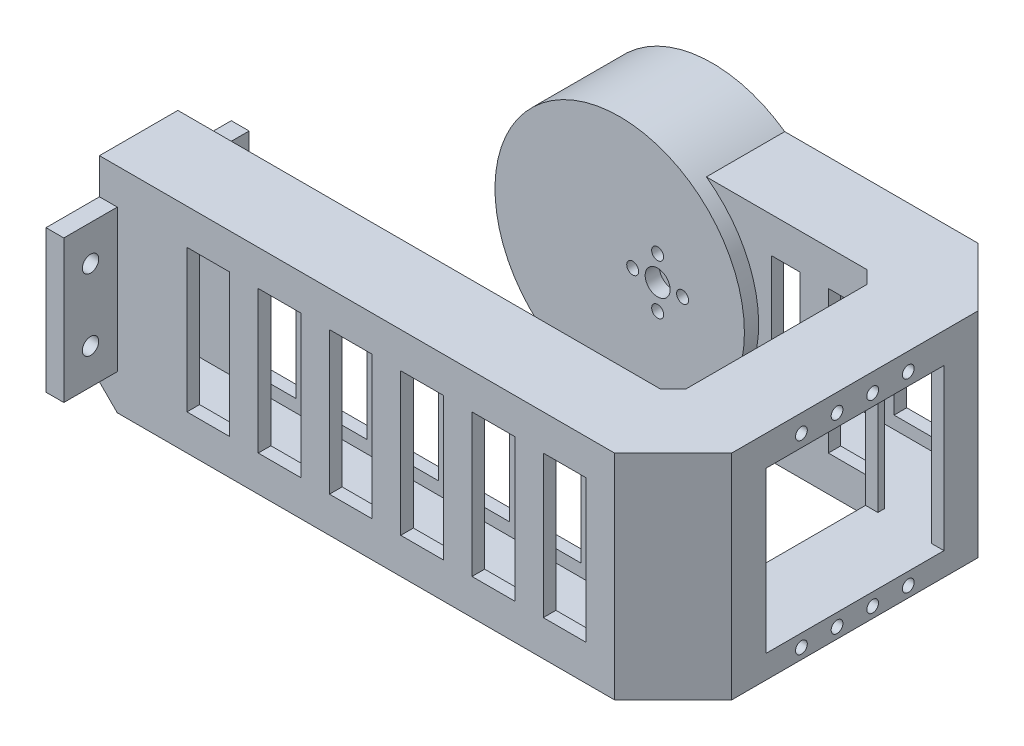
SolidWorks part; units mm, degrees
ref_plane "Plan de face" through (0, 0, 0) normal (0, 0, 1) x (1, 0, 0)
ref_plane "Plan de dessus" through (0, 0, 0) normal (0, 1, 0) x (1, 0, 0)
ref_plane "Plan de droite" through (0, 0, 0) normal (1, 0, 0) x (0, 0, -1)
sketch "Esquisse1" plane through (0, 0, 0) normal (0, 0, 1) x (1, 0, 0)
  circle A0 centre (0, 0) radius 35
  dimension "D1" = 70
extrude "Boss.-Extru.2" add sketch "Esquisse1" along normal blind 26
sketch "Esquisse4" plane through (0, 0, 0) normal (1, 0, 0) x (0, 0, -1)
  line L0 (-18.5, 16.6184) -> (-18.5, -18.3816)
  line L1 (-21.7349, 0) -> (0, 0) construction
  line L2 (-3.5, 16.6184) -> (-3.5, -18.3816)
  line L4 (0, 36.85) -> (0, -36.85) construction
  arc A0 (-18.5, 16.6184) -> (-3.5, 16.6184) centre (-11, 6) cw
  arc A1 (-18.5, -18.3816) -> (-3.5, -18.3816) centre (-11, -7.7632) ccw
  dimension "D3" = 3.5
  dimension "D4" = 13
  dimension "D7" = 6
  dimension "D2" = 15
  dimension "D1" = 15
  dimension "D5" = 35
  dimension "D6" = 0
  dimension "D8" = 16.6184
  dimension "D9" = 7.7632
extrude "Enlèv. mat.-Extru.6" cut sketch "Esquisse4" along normal blind 35
sketch "Esquisse5" plane through (0, 0, 0) normal (1, 0, 0) x (0, 0, -1)
  line L0 (-18.55, 20) -> (-18.55, -25)
  line L1 (-18.55, -25) -> (-3.55, -25)
  line L2 (-3.55, -25) -> (-3.55, 20)
  line L3 (-18.55, 20) -> (-3.55, 20)
  line L4 (0, 55) -> (0, -55) construction
  line L5 (-26, -35) -> (0, -35) construction
  line L7 (-22, 28.5) -> (0, 28.5)
  line L8 (-22, 28.5) -> (-22, -31.5)
  line L9 (-22, -31.5) -> (0, -31.5)
  line L10 (0, 28.5) -> (0, -31.5)
  line L11 (-22, 28.5) -> (0, -31.5) construction
  line L12 (-22, -31.5) -> (0, 28.5) construction
  point P8 (-11, -1.5)
  dimension "D1" = 15
  dimension "D2" = 3.55
  dimension "D3" = 45
  dimension "D4" = 10
  dimension "D5" = 0
  dimension "D6" = 3.5
  dimension "D7" = 60
  dimension "D8" = 22
sketch3d "Esquisse3D6"
  line L0 (0, -1.5, 11) -> (70, -1.5, 11)
  line L1 (70, -1.5, 11) -> (80, -1.5, 21)
  line L2 (80, -1.5, 81) -> (70, -1.5, 91)
  line L6 (80, -1.5, 21) -> (80, -1.5, 81)
  line L7 (70, -1.5, 91) -> (-70, -1.5, 91)
  point P1 (80, -1.5, 11)
  point P3 (80, -1.5, 91)
  dimension "D1" = 80
  dimension "D3" = 80
  dimension "D4" = 150
sweep "Balayage16" add profiles "Esquisse5" path "Esquisse3D6"
sketch "Esquisse7" plane through (0, 0, 0) normal (1, 0, 0) x (0, 0, -1)
  line L0 (55, 0) -> (-55, 0) construction
  line L1 (0, -30) -> (-22, -30)
  line L2 (0, -30) -> (0, 30)
  line L3 (0, 30) -> (-22, 30)
  line L4 (-22, -30) -> (-22, 30)
  line L5 (0, -30) -> (-22, 30) construction
  line L6 (0, 30) -> (-22, -30) construction
  line L7 (0, -35) -> (0, 35) construction
  line L8 (-26, -35) -> (0, -35) construction
  line L9 (-4, 20) -> (-19, 20)
  line L10 (-4, 20) -> (-4, -25)
  line L11 (-4, -25) -> (-19, -25)
  line L12 (-19, 20) -> (-19, -25)
  point P0 (-11, 0)
  dimension "D1" = 0
  dimension "D2" = 22
  dimension "D3" = 60
  dimension "D4" = 4
  dimension "D5" = 10
  dimension "D6" = 45
  dimension "D7" = 15
extrude "Enlèv. mat.-Extru.11" cut sketch "Esquisse7" along normal blind 11
sketch "Esquisse9" plane through (0, 0, 0) normal (0, 0, -1) x (-1, 0, 0)
  circle A0 centre (0, 0) radius 31.5
  dimension "D1" = 63
extrude "Enlèv. mat.-Extru.12" cut sketch "Esquisse9" against normal blind 18.8
sketch "Esquisse10" plane through (0, 0, 26) normal (0, 0, 1) x (1, 0, 0)
  line L0 (0, 8.8008) -> (0, -8.9311) construction
  line L1 (55, 0) -> (-55, 0) construction
  line L2 (-21, 11) -> (-21, -11) construction
  line L3 (-21, -11) -> (21, -11) construction
  line L4 (-21, 11) -> (21, 11) construction
  line L5 (21, 11) -> (21, -11) construction
  line L6 (3.65, 0) -> (17.65, 0) construction
  line L7 (-21, -11) -> (21, 11) construction
  line L8 (-21, 11) -> (21, -11) construction
  line L9 (10.65, 0) -> (10.65, 8.8008) construction
  line L10 (10.65, 0) -> (10.65, -8.9311) construction
  line L11 (12.325, -7) -> (6.1002, -7) construction
  line L12 (12.325, 7) -> (6.6662, 7) construction
  circle A0 centre (10.65, 0) radius 3.5
  circle A2 centre (17.65, 0) radius 1.675
  circle A3 centre (3.65, 0) radius 1.675
  circle A5 centre (10.65, -7) radius 1.675
  circle A6 centre (10.65, 7) radius 1.675
  point P4 (0, 0)
  dimension "D2" = 7
  dimension "D9" = 7
  dimension "D10" = 3.35
  dimension "D12" = 3.35
  dimension "D14" = 3.35
  dimension "D5" = 3.35
  dimension "D7" = 7
  dimension "D8" = 7
  dimension "D6" = 7
  dimension "D15" = 3.35
  dimension "D3" = 22
  dimension "D4" = 42
extrude "Enlèv. mat.-Extru.13" cut sketch "Esquisse10" against normal blind 10
sketch "Esquisse12" plane through (0, 0, 0) normal (1, 0, 0) x (0, 0, -1)
  line L0 (-76, 20) -> (-26, 20)
  line L1 (-26, 20) -> (-26, -25)
  line L2 (-26, -25) -> (-76, -25)
  line L3 (-16.4437, 28.5) -> (-85.5563, 28.5) construction
  line L4 (-16.4437, -31.5) -> (-85.5563, -31.5) construction
  line L14 (-76, 20) -> (-76, -25)
  circle A0 centre (-66, -28.5) radius 1.65
  circle A1 centre (-36, -28.5) radius 1.65
  circle A2 centre (-46, -28.5) radius 1.65
  circle A3 centre (-56, -28.5) radius 1.65
  circle A4 centre (-66, 23.5) radius 1.65
  circle A5 centre (-56, 23.5) radius 1.65
  circle A6 centre (-46, 23.3) radius 1.65
  circle A7 centre (-36, 23.5) radius 1.65
  dimension "D5" = 3.3
  dimension "D6" = 3.3
  dimension "D11" = 3.3
  dimension "D12" = 3.3
  dimension "D17" = 3.3
  dimension "D18" = 3.3
  dimension "D19" = 3.3
  dimension "D20" = 3.3
  dimension "D1" = 8.5
  dimension "D2" = 6.5
  dimension "D3" = 26
  dimension "D4" = 50
  dimension "D7" = 3.5
  dimension "D8" = 3.5
  dimension "D9" = 10
  dimension "D10" = 10
  dimension "D13" = 3.5
  dimension "D14" = 3.5
  dimension "D15" = 10
  dimension "D16" = 10
  dimension "D21" = 10
  dimension "D22" = 10
  dimension "D23" = 10
  dimension "D24" = 10
  dimension "D25" = 3.5
  dimension "D26" = 3.5
  dimension "D27" = 3.3
  dimension "D28" = 3.5
extrude "Enlèv. mat.-Extru.16" cut sketch "Esquisse12" along normal blind 100
sketch "Esquisse14" plane through (0, 0, 0) normal (0, 0, -1) x (-1, 0, 0)
  line L0 (-74.5563, -31.5) -> (-74.5563, 28.5) construction
  line L1 (-54.5563, 18.5) -> (-66.5563, 18.5)
  line L2 (-66.5563, 18.5) -> (-66.5563, -21.5)
  line L3 (-66.5563, -21.5) -> (-54.5563, -21.5)
  line L4 (-74.5563, -31.5) -> (70, -31.5) construction
  line L5 (-74.5563, -31.5) -> (-15.2561, -31.5) construction
  line L6 (-46.5563, -21.5) -> (-38.5563, -21.5)
  line L7 (-46.5563, -21.5) -> (-46.5563, 18.5)
  line L8 (-46.5563, 18.5) -> (-38.5563, 18.5)
  line L9 (-38.5563, -21.5) -> (-38.5563, 18.5)
  line L10 (-54.5563, 18.5) -> (-54.5563, -21.5)
  line L11 (-46.5563, -21.5) -> (-38.5563, 18.5) construction
  line L12 (-46.5563, 18.5) -> (-38.5563, -21.5) construction
  point P4 (-42.5563, -1.5)
  dimension "D1" = 8
  dimension "D2" = 12
  dimension "D3" = 10
  dimension "D4" = 8
  dimension "D5" = 8
  dimension "D6" = 10
  dimension "D7" = 40
  dimension "D10" = 40
extrude "Enlèv. mat.-Extru.17" cut sketch "Esquisse14" against normal blind 40
chamfer "Chanfrein1" distance 5 angle 45 1 edges at (-70, -31.5, 91)
sketch "Esquisse18" plane through (0, 0, 102) normal (0, 0, 1) x (1, 0, 0)
  line L1 (54.5563, 18.5) -> (66.5563, 18.5)
  line L2 (66.5563, -21.5) -> (54.5563, -21.5)
  line L3 (-13.4437, 18.5) -> (-13.4437, -21.5)
  line L4 (66.5563, 18.5) -> (66.5563, -21.5)
  line L5 (34.5563, 18.5) -> (46.5563, 18.5)
  line L6 (54.5563, 18.5) -> (54.5563, -21.5)
  line L7 (34.5563, -21.5) -> (46.5563, -21.5)
  line L8 (74.5563, -31.5) -> (-65, -31.5) construction
  line L9 (-13.4437, -21.5) -> (-25.4437, -21.5)
  line L10 (74.5563, 28.5) -> (-70, 28.5) construction
  line L11 (14.5563, 18.5) -> (26.5563, 18.5)
  line L12 (-5.4437, 18.5) -> (6.5563, 18.5)
  line L13 (-5.4437, 18.5) -> (-5.4437, -21.5)
  line L14 (-5.4437, -21.5) -> (6.5563, -21.5)
  line L15 (6.5563, 18.5) -> (6.5563, -21.5)
  line L16 (26.5563, -21.5) -> (14.5563, -21.5)
  line L17 (14.5563, 18.5) -> (14.5563, -21.5)
  line L18 (-25.4437, -21.5) -> (-25.4437, 18.5)
  line L19 (-25.4437, 18.5) -> (-13.4437, 18.5)
  line L20 (74.5563, 28.5) -> (74.5563, -31.5) construction
  line L22 (-45.4437, -21.5) -> (-33.4437, -21.5)
  line L23 (26.5563, 18.5) -> (26.5563, -21.5)
  line L24 (-45.4437, -21.5) -> (-45.4437, 18.5)
  line L25 (34.5563, 18.5) -> (34.5563, -21.5)
  line L26 (-45.4437, 18.5) -> (-33.4437, 18.5)
  line L27 (-33.4437, -21.5) -> (-33.4437, 18.5)
  line L31 (46.5563, 18.5) -> (46.5563, -21.5)
  dimension "D1" = 40
  dimension "D2" = 40
  dimension "D3" = 12
  dimension "D4" = 10
  dimension "D5" = 12
  dimension "D6" = 8
  dimension "D7" = 12
  dimension "D8" = 10
  dimension "D9" = 12
  dimension "D10" = 10
  dimension "D11" = 40
  dimension "D12" = 12
  dimension "D13" = 8
  dimension "D14" = 10
  dimension "D15" = 10
  dimension "D16" = 8
  dimension "D17" = 40
  dimension "D18" = 10
  dimension "D19" = 40
  dimension "D20" = 8
  dimension "D21" = 12
  dimension "D23" = 8
  dimension "D24" = 40
  dimension "D27" = 8
  dimension "D28" = 40
extrude "Enlèv. mat.-Extru.19" cut sketch "Esquisse18" against normal blind 25
sketch "Esquisse19" plane through (0, 0, 102) normal (0, 0, 1) x (1, 0, 0)
  line L0 (74.5563, -31.5) -> (-65, -31.5) construction
  line L1 (-70, 18.5) -> (-65, 18.5)
  line L2 (-70, 18.5) -> (-70, -21.5)
  line L3 (-70, -21.5) -> (-65, -21.5)
  line L4 (-65, 18.5) -> (-65, -21.5)
  line L7 (-70, -26.5) -> (-70, 28.5) construction
  dimension "D1" = 10
  dimension "D2" = 40
  dimension "D3" = 0
  dimension "D4" = 5
extrude "Boss.-Extru.3" add sketch "Esquisse19" along normal blind 15
sketch "Esquisse20" plane through (0, 0, 80) normal (0, 0, -1) x (-1, 0, 0)
  line L0 (70, 28.5) -> (70, -26.5) construction
  line L1 (65, 18.5) -> (70, 18.5)
  line L2 (65, 18.5) -> (65, -21.5)
  line L3 (65, -21.5) -> (70, -21.5)
  line L4 (70, 18.5) -> (70, -21.5)
  line L5 (-65.4437, -31.5) -> (65, -31.5) construction
  dimension "D1" = 0
  dimension "D2" = 5
  dimension "D3" = 40
  dimension "D4" = 10
extrude "Boss.-Extru.4" add sketch "Esquisse20" along normal blind 15
sketch "Esquisse21" plane through (-65, 0, 0) normal (1, 0, 0) x (0, 0, -1)
  line L0 (-102, -21.5) -> (-102, 18.5) construction
  line L1 (-117, -21.5) -> (-102, -21.5) construction
  line L2 (-117, 18.5) -> (-102, 18.5) construction
  line L3 (-65, 18.5) -> (-80, 18.5) construction
  line L4 (-65, -21.5) -> (-80, -21.5) construction
  line L5 (-80, 18.5) -> (-80, -21.5) construction
  line L7 (-98.45, 20) -> (-98.45, -25) construction
  circle A0 centre (-109.5, 8.5) radius 2.3
  circle A1 centre (-109.5, -11.5) radius 2.3
  circle A2 centre (-72.5, 8.5) radius 2.3
  circle A3 centre (-72.5, -11.5) radius 2.3
  dimension "D1" = 4.6
  dimension "D2" = 4.6
  dimension "D7" = 4.6
  dimension "D8" = 4.6
  dimension "D3" = 7.5
  dimension "D4" = 7.5
  dimension "D5" = 10
  dimension "D6" = 10
  dimension "D9" = 10
  dimension "D10" = 10
  dimension "D11" = 7.5
  dimension "D12" = 7.5
  dimension "D13" = 20
  dimension "D14" = 11.05
extrude "Enlèv. mat.-Extru.20" cut sketch "Esquisse21" against normal blind 15
sketch "Esquisse22" plane through (37.2782, 0, -37.2782) normal (0.7071, 0, -0.7071) x (-0.7071, 0, -0.7071)
  line L0 (-69.7193, 18.5) -> (-69.7193, -21.5)
  line L1 (-69.7193, 18.5) -> (-59.7193, 18.5)
  line L2 (-69.7193, -21.5) -> (-59.7193, -21.5)
  line L3 (-59.7193, -21.5) -> (-59.7193, 18.5)
  line L4 (-52.7193, -31.5) -> (-75.9741, -31.5) construction
  line L5 (-52.7193, -31.5) -> (-52.7193, 28.5) construction
  dimension "D1" = 40
  dimension "D2" = 10
  dimension "D3" = 10
  dimension "D4" = 7
extrude "Enlèv. mat.-Extru.21" cut sketch "Esquisse22" against normal blind 10
